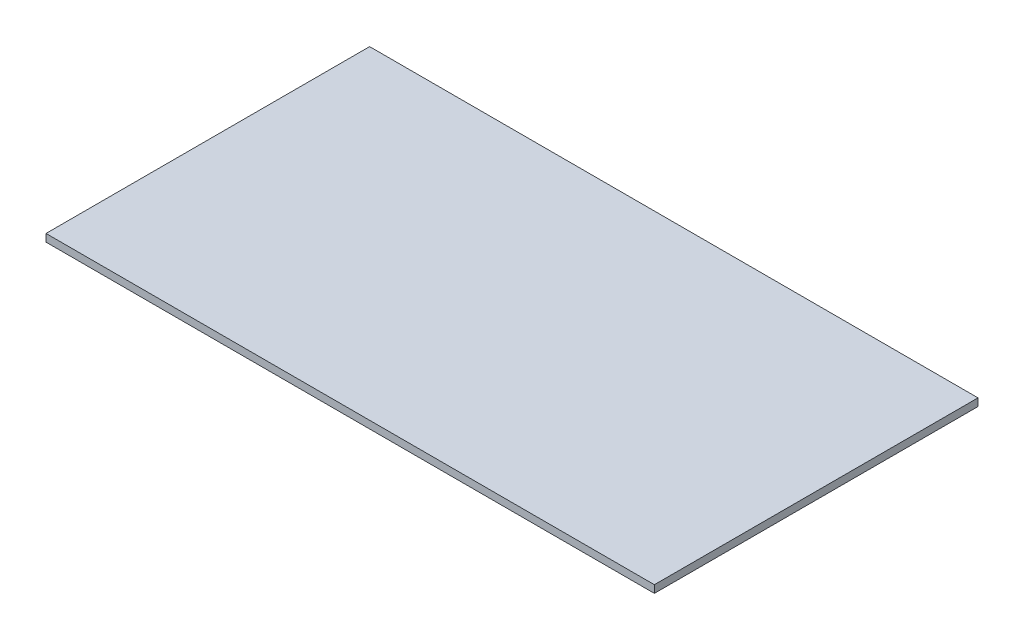
SolidWorks part; units mm, degrees
ref_plane "Front" through (0, 0, 0) normal (0, 0, 1) x (1, 0, 0)
ref_plane "Top" through (0, 0, 0) normal (0, 1, 0) x (1, 0, 0)
ref_plane "Right" through (0, 0, 0) normal (1, 0, 0) x (0, 0, -1)
sketch "Sketch1" plane through (0, 0, 0) normal (0, 1, 0) x (1, 0, 0)
  line L1 (-63.5, -33.7766) -> (63.5, -33.7766)
  line L2 (-63.5, -33.7766) -> (-63.5, 33.7766)
  line L3 (-63.5, 33.7766) -> (63.5, 33.7766)
  line L4 (63.5, -33.7766) -> (63.5, 33.7766)
  line L5 (-63.5, -33.7766) -> (63.5, 33.7766) construction
  line L6 (-63.5, 33.7766) -> (63.5, -33.7766) construction
  point P0 (0, 0)
  dimension "D1" = 127
extrude "Boss-Extrude1" add sketch "Sketch1" along normal blind 1.5748
